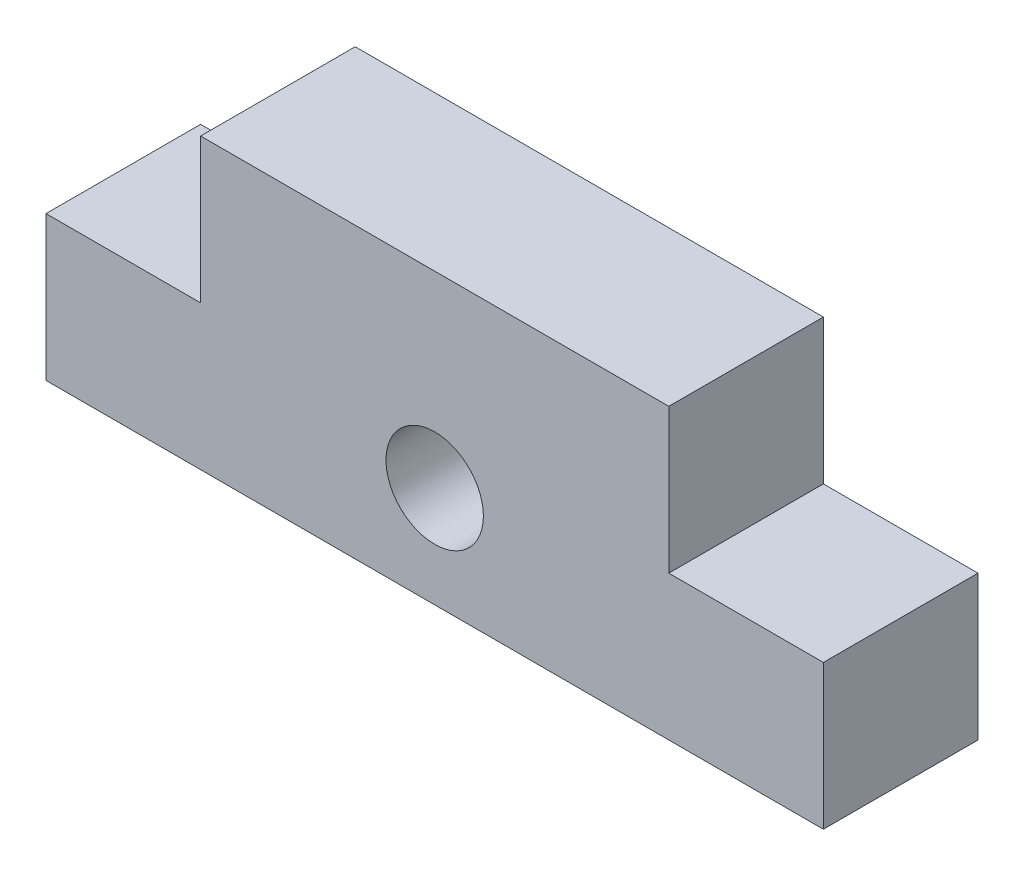
SolidWorks part; units mm, degrees
ref_plane "Front Plane" through (0, 0, 0) normal (0, 0, 1) x (1, 0, 0)
ref_plane "Top Plane" through (0, 0, 0) normal (0, 1, 0) x (1, 0, 0)
ref_plane "Right Plane" through (0, 0, 0) normal (1, 0, 0) x (0, 0, -1)
sketch "Model" plane through (0, 0, 0) normal (0, 0, 1) x (1, 0, 0)
  line L599 (5.35, 10) -> (5.35, 5)
  line L600 (21.55, 10) -> (5.35, 10)
  line L601 (21.55, 5) -> (21.55, 10)
  line L602 (26.9, 5) -> (21.55, 5)
  line L603 (26.9, 0) -> (26.9, 5)
  line L604 (0, 0) -> (26.9, 0)
  line L605 (0, 5) -> (0, 0)
  line L606 (5.35, 5) -> (0, 5)
  circle A145 centre (13.45, 3.5) radius 1.685
extrude "Boss-Extrude1" add sketch "Model" along normal blind 5.35
